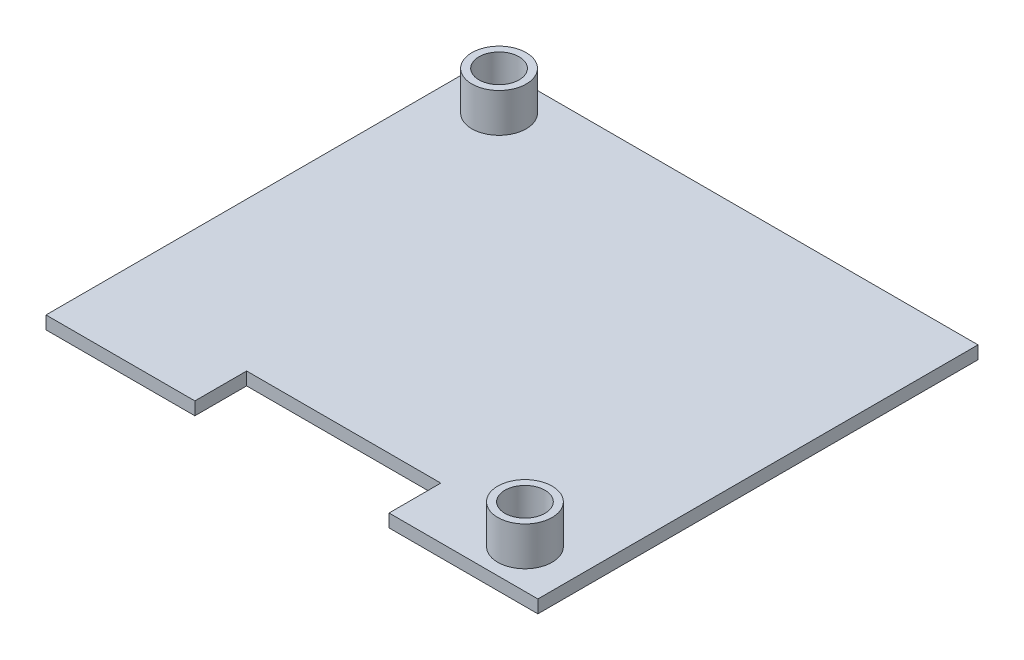
SolidWorks part; units mm, degrees
ref_plane "정면" through (0, 0, 0) normal (0, 0, 1) x (1, 0, 0)
ref_plane "윗면" through (0, 0, 0) normal (0, 1, 0) x (1, 0, 0)
ref_plane "우측면" through (0, 0, 0) normal (1, 0, 0) x (0, 0, -1)
sketch "스케치1" plane through (0, 0, 0) normal (0, 1, 0) x (1, 0, 0)
  line L1 (-19, 17) -> (19, 17)
  line L2 (-19, 17) -> (-19, -17)
  line L3 (-19, -17) -> (19, -17)
  line L4 (19, 17) -> (19, -17)
  line L5 (-19, 17) -> (19, -17) construction
  line L6 (-19, -17) -> (19, 17) construction
  point P0 (0, 0)
  dimension "D1" = 38
  dimension "D2" = 34
extrude "Middle_plate" add sketch "스케치1" along normal blind 1
sketch "스케치2" plane through (0, 1, 0) normal (0, 1, 0) x (1, 0, 0)
  line L1 (-15, 14) -> (15, 14)
  line L2 (-15, 14) -> (-15, -14)
  line L3 (-15, -14) -> (15, -14)
  line L4 (15, 14) -> (15, -14)
  line L5 (-15, 14) -> (15, -14) construction
  line L6 (-15, -14) -> (15, 14) construction
  circle A0 centre (-15, 14) radius 1.55
  circle A1 centre (15, -14) radius 2.1
  circle A2 centre (-15, 14) radius 2.1
  circle A3 centre (15, -14) radius 1.55
  point P0 (0, 0)
  dimension "D3" = 3.1
  dimension "D4" = 4.2
  dimension "D1" = 30
  dimension "D2" = 28
extrude "Middle_pillar" add sketch "스케치2" along normal blind 3 contours A3 L3 A1 L4 | A3 L4 A1 L3 | L2 A2 L1 A0 | L1 A2 L2 A0
sketch "스케치3" plane through (0, 0, 0) normal (0, -1, 0) x (1, 0, 0)
  line L5 (-7.5, 17) -> (7.5, 17)
  line L6 (-7.5, 17) -> (-7.5, 13)
  line L7 (-7.5, 13) -> (7.5, 13)
  line L8 (7.5, 17) -> (7.5, 13)
  line L9 (-7.5, 17) -> (7.5, 13) construction
  line L10 (19, -17) -> (19, 17)
  line L11 (19, 17) -> (-19, 17)
  line L12 (-19, 17) -> (-19, -17)
  line L13 (-19, -17) -> (19, -17)
  line L14 (19, -17) -> (19, 17)
  line L15 (19, 17) -> (-19, 17)
  line L16 (-19, 17) -> (-19, -17)
  line L17 (-19, -17) -> (19, -17)
  line L18 (-7.5, 13) -> (7.5, 17) construction
  point P0 (0, 15)
  line M10 (19, 17) -> (-19, 17)
  dimension "D2" = 15
  dimension "D3" = 4
  dimension "D1" = 0
extrude "C_cut" cut sketch "스케치3" against normal up to next contours L8 L6 L7 M10
